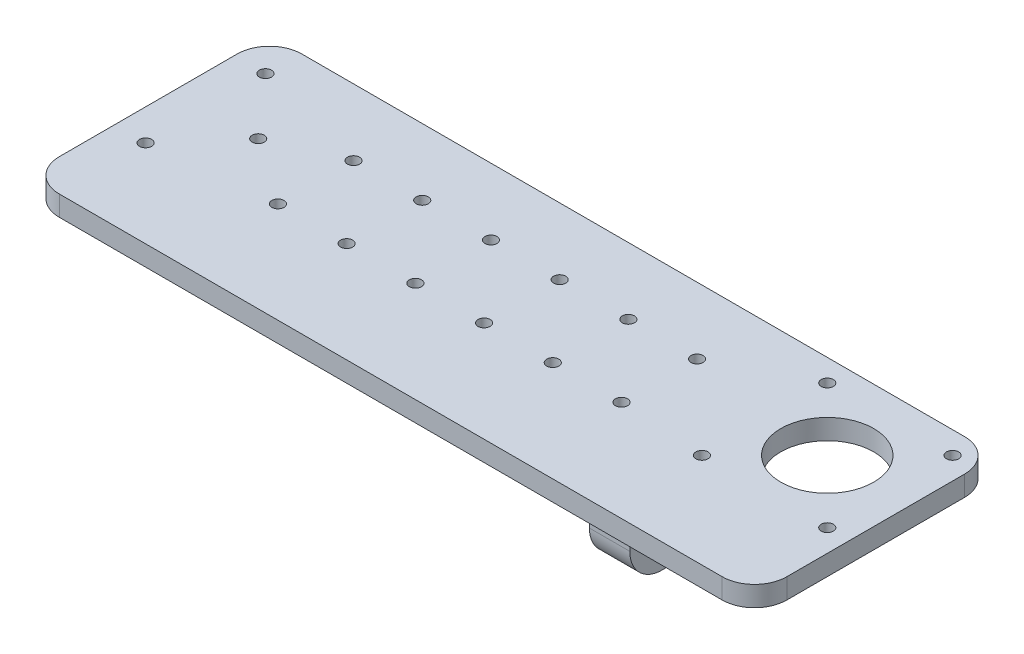
SolidWorks part; units mm, degrees
ref_plane "정면" through (0, 0, 0) normal (0, 0, 1) x (1, 0, 0)
ref_plane "윗면" through (0, 0, 0) normal (0, 1, 0) x (1, 0, 0)
ref_plane "우측면" through (0, 0, 0) normal (1, 0, 0) x (0, 0, -1)
sketch "스케치1" plane through (0, 0, 0) normal (0, 1, 0) x (1, 0, 0)
  line L0 (-53.3677, 28.2576) -> (-53.3677, -31.7424)
  line L1 (-53.3677, -31.7424) -> (126.6323, -31.7424)
  line L2 (126.6323, -31.7424) -> (126.6323, 28.2576)
  line L3 (126.6323, 28.2576) -> (-53.3677, 28.2576)
  circle A0 centre (105.6323, 7.2576) radius 11
  circle A2 centre (90.1323, 22.7576) radius 1.5
  circle A3 centre (121.1323, 22.7576) radius 1.5
  circle A4 centre (90.1323, -8.2424) radius 1.5
  circle A5 centre (121.1323, -8.2424) radius 1.5
  circle A6 centre (-32.6178, 4.7126) radius 1.5
  circle A7 centre (-45.6544, 19.5487) radius 1.5
  circle A8 centre (-45.6544, -10.1235) radius 1.5
  dimension "D4" = 31
  dimension "D1" = 180
  dimension "D3" = 60
  dimension "D5" = 31
extrude "보스-돌출3" add sketch "스케치1" along normal blind 5
sketch "스케치2" plane through (0, 5, 0) normal (0, 1, 0) x (1, 0, 0)
  line L2 (84.7825, 18.2576) -> (74.7825, 18.2576)
  line L3 (74.7825, 18.2576) -> (74.7825, -1.7424)
  line L4 (74.7825, -1.7424) -> (84.7825, -1.7424)
  line L5 (84.7825, -1.7424) -> (84.7825, 18.2576)
extrude "보스-돌출4" add sketch "스케치2" along normal blind 20
sketch "스케치4" plane through (74.7825, 0, 0) normal (-1, 0, 0) x (0, 0, 1)
  line L0 (1.7424, 25) -> (-8.2576, 25)
  line L1 (-18.2576, 25) -> (1.7424, 25) construction
  line L2 (-8.2576, 25) -> (-8.2576, 15)
  circle A0 centre (-8.2576, 15) radius 4
extrude "컷-돌출1" cut sketch "스케치4" against normal blind 20
sketch "스케치7" plane through (84.7825, 0, 0) normal (1, 0, 0) x (0, 0, -1)
  line L0 (18.2576, 25) -> (15.2576, 25)
  line L1 (-1.7424, 25) -> (18.2576, 25) construction
  line L2 (15.2576, 25) -> (15.2576, 5)
  line L3 (-1.7424, 5) -> (18.2576, 5) construction
  line L4 (15.2576, 5) -> (18.2576, 5)
  line L5 (18.2576, 5) -> (18.2576, 25)
  line L6 (-1.7424, 25) -> (1.2576, 25)
  line L7 (1.2576, 25) -> (1.2576, 5)
  line L8 (1.2576, 5) -> (-1.7424, 5)
  line L9 (-1.7424, 5) -> (-1.7424, 25)
  dimension "D1" = 3
  dimension "D2" = 3
sketch "스케치8" plane through (84.7825, 0, 0) normal (1, 0, 0) x (0, 0, -1)
  line L1 (15.2576, 25) -> (18.2576, 25)
  line L2 (15.2576, 25) -> (15.2576, 5)
  line L3 (15.2576, 5) -> (18.2576, 5)
  line L4 (18.2576, 25) -> (18.2576, 5)
  line L5 (1.2576, 25) -> (-1.7424, 25)
  line L6 (1.2576, 25) -> (1.2576, 5)
  line L7 (1.2576, 5) -> (-1.7424, 5)
  line L8 (-1.7424, 25) -> (-1.7424, 5)
extrude "컷-돌출4" cut sketch "스케치8" against normal blind 10
sketch "스케치9" plane through (84.7825, 0, 0) normal (1, 0, 0) x (0, 0, -1)
  line L0 (8.2576, 15) -> (1.7576, 15)
  line L1 (1.7576, 15) -> (1.7576, 5)
  line L2 (1.2576, 25) -> (15.2576, 25)
  line L3 (1.2576, 25) -> (1.2576, 5)
  line L4 (1.2576, 5) -> (15.2576, 5)
  line L5 (15.2576, 25) -> (15.2576, 5)
  line L6 (1.7576, 5) -> (1.7576, 25)
  line L8 (1.7576, 25) -> (-12.2424, 25)
  line L9 (1.7576, 25) -> (1.7576, 5)
  line L10 (1.7576, 5) -> (-12.2424, 5)
  line L11 (-12.2424, 25) -> (-12.2424, 5)
  circle A0 centre (-5.2424, 15) radius 4
  dimension "D3" = 8
  dimension "D1" = 14
  dimension "D2" = 6.5
  dimension "D4" = 7
sketch "스케치10" plane through (84.7825, 0, 0) normal (1, 0, 0) x (0, 0, -1)
  line L1 (-12.2424, 25) -> (1.7576, 25)
  line L2 (-12.2424, 25) -> (-12.2424, 5)
  line L3 (-12.2424, 5) -> (1.7576, 5)
  line L4 (1.7576, 25) -> (1.7576, 5)
extrude "보스-돌출5" add sketch "스케치10" against normal blind 10
extrude "컷-돌출5" cut sketch "스케치9" against normal blind 10 contours A0
sketch "스케치11" plane through (84.7825, 0, 0) normal (1, 0, 0) x (0, 0, -1)
  line L1 (-12.2424, 5) -> (15.2576, 5) construction
  line L3 (1.7576, 5) -> (15.2576, 5)
  line L4 (1.7576, 5) -> (1.7576, 25)
  line L5 (1.7576, 25) -> (15.2576, 25)
  line L6 (15.2576, 5) -> (15.2576, 25)
sketch "스케치12" plane through (84.7825, 0, 0) normal (1, 0, 0) x (0, 0, -1)
  line L1 (1.7576, 25) -> (15.2576, 25)
  line L2 (1.7576, 25) -> (1.7576, 5)
  line L3 (1.7576, 5) -> (15.2576, 5)
  line L4 (15.2576, 25) -> (15.2576, 5)
extrude "컷-돌출6" cut sketch "스케치12" against normal blind 10
sketch "스케치14" plane through (0, 5, 0) normal (0, 1, 0) x (1, 0, 0)
  line L0 (105.6323, 7.2576) -> (105.6323, 0.7576)
  line L1 (84.7825, 1.7576) -> (105.6323, 1.7576)
  dimension "D1" = 6.5
sketch "스케치15" plane through (84.7825, 0, 0) normal (1, 0, 0) x (0, 0, -1)
  line L0 (-12.2424, 5) -> (1.7576, 5) construction
  line L1 (1.7576, 25) -> (0.7576, 25)
  line L2 (1.7576, 25) -> (1.7576, 5)
  line L3 (1.7576, 5) -> (0.7576, 5)
  line L4 (0.7576, 25) -> (0.7576, 5)
  dimension "D1" = 1
extrude "컷-돌출7" cut sketch "스케치15" against normal blind 10
fillet "필렛5" radius 5 2 edges at (79.7825, 25, -0.7576) (79.7825, 25, 12.2424)
sketch "스케치16" plane through (0, 5, 0) normal (0, 1, 0) x (1, 0, 0)
  line L0 (105.6323, 7.2576) -> (105.6323, 0.7576)
sketch "스케치17" plane through (0, 5, 0) normal (0, 1, 0) x (1, 0, 0)
  line L0 (105.6323, 7.2576) -> (105.6323, -5.7424)
  line L1 (105.6323, -5.7424) -> (84.7825, -5.7424)
  line L2 (84.7825, -12.2424) -> (84.7825, 0.7576) construction
  line L3 (74.7825, 0.7576) -> (74.7825, -12.2424) construction
  line L4 (84.7825, -5.7424) -> (74.7825, -5.7424)
  line L5 (84.7825, -5.7424) -> (84.7825, 3.2576)
  line L6 (84.7825, 3.2576) -> (74.7825, 3.2576)
  line L7 (74.7825, -5.7424) -> (74.7825, 3.2576)
  line L9 (84.7825, -5.7424) -> (74.7825, -5.7424)
  line L10 (84.7825, -5.7424) -> (84.7825, -14.7424)
  line L11 (84.7825, -14.7424) -> (74.7825, -14.7424)
  line L12 (74.7825, -5.7424) -> (74.7825, -14.7424)
  dimension "D1" = 9
  dimension "D2" = 9
sketch "스케치20" plane through (74.7825, 0, 0) normal (-1, 0, 0) x (0, 0, 1)
  line L1 (-3.2576, 5) -> (-1.0985, 5)
  line L2 (-3.2576, 5) -> (-3.2576, 27.106)
  line L3 (-3.2576, 27.106) -> (-1.0985, 27.106)
  line L4 (-1.0985, 5) -> (-1.0985, 27.106)
sketch "스케치21" plane through (0, 5, 0) normal (0, 1, 0) x (1, 0, 0)
  line L1 (84.7825, -14.7424) -> (74.7825, -14.7424)
  line L2 (84.7825, -14.7424) -> (84.7825, 3.2576)
  line L3 (84.7825, 3.2576) -> (74.7825, 3.2576)
  line L4 (74.7825, -14.7424) -> (74.7825, 3.2576)
extrude "보스-돌출6" add sketch "스케치21" along normal blind 20
sketch "스케치23" plane through (84.7825, 0, 0) normal (1, 0, 0) x (0, 0, -1)
  line L1 (-14.7424, 25) -> (3.2576, 25) construction
  circle A0 centre (-5.7424, 15) radius 4
  dimension "D1" = 10
extrude "컷-돌출9" cut sketch "스케치23" against normal blind 20
fillet "필렛8" radius 8 1 edges at (79.7825, 5, 14.7424)
sketch "스케치24" plane through (0, 5, 0) normal (0, 1, 0) x (1, 0, 0)
  line L0 (105.6323, 7.2576) -> (105.6323, 0.7576)
sketch "스케치25" plane through (0, 5, 0) normal (0, 1, 0) x (1, 0, 0)
  line L1 (84.7825, 3.2576) -> (73.4713, 3.2576)
  line L2 (84.7825, 3.2576) -> (84.7825, 1.7576)
  line L3 (84.7825, 1.7576) -> (73.4713, 1.7576)
  line L4 (73.4713, 3.2576) -> (73.4713, 1.7576)
extrude "컷-돌출10" cut sketch "스케치25" along normal blind 20
fillet "필렛9" radius 8 2 edges at (79.7825, 25, 14.7424) (79.7825, 25, -1.7576)
sketch "스케치28" plane through (0, 5, 0) normal (0, 1, 0) x (1, 0, 0)
  line L1 (84.7825, 1.7576) -> (74.7825, 1.7576)
  line L2 (84.7825, 1.7576) -> (84.7825, -14.7424)
  line L3 (84.7825, -14.7424) -> (74.7825, -14.7424)
  line L4 (74.7825, 1.7576) -> (74.7825, -14.7424)
extrude "보스-돌출7" add sketch "스케치28" against normal blind 25
sketch "스케치29" plane through (84.7825, 0, 0) normal (1, 0, 0) x (0, 0, -1)
  line L0 (-1.7424, 15) -> (-1.7424, -20)
  line L1 (-14.7424, -20) -> (1.7576, -20) construction
  line L2 (-9.7424, 15) -> (-9.7424, -20)
  line L3 (-5.7424, 15) -> (-5.7424, -15.838)
  circle A0 centre (-5.7424, 15) radius 4 construction
  circle A1 centre (-5.7424, -10) radius 4
  dimension "D1" = 10
sketch "스케치30" plane through (84.7825, 0, 0) normal (1, 0, 0) x (0, 0, -1)
  circle A0 centre (-5.7424, -10) radius 3.9991
sketch "스케치31" plane through (0, 5, 0) normal (0, 1, 0) x (1, 0, 0)
  line L1 (85.7781, -25.2023) -> (58.1481, -25.2023)
  line L2 (85.7781, -25.2023) -> (85.7781, 8.1404)
  line L3 (85.7781, 8.1404) -> (58.1481, 8.1404)
  line L4 (58.1481, -25.2023) -> (58.1481, 8.1404)
extrude "컷-돌출12" cut sketch "스케치31" along normal blind 20
sketch "스케치33" plane through (0, 0, 14.7424) normal (0, 0, 1) x (1, 0, 0)
  line L1 (84.7825, -20) -> (74.7825, -20)
  line L2 (84.7825, -20) -> (84.7825, 0)
  line L3 (84.7825, 0) -> (74.7825, 0)
  line L4 (74.7825, -20) -> (74.7825, 0)
extrude "보스-돌출8" add sketch "스케치33" along normal blind 6
sketch "스케치34" plane through (0, 0, -1.7576) normal (0, 0, -1) x (-1, 0, 0)
  line L1 (-74.7825, -20) -> (-84.7825, -20)
  line L2 (-74.7825, -20) -> (-74.7825, 0)
  line L3 (-74.7825, 0) -> (-84.7825, 0)
  line L4 (-84.7825, -20) -> (-84.7825, 0)
extrude "컷-돌출13" cut sketch "스케치34" against normal blind 6
sketch "스케치35" plane through (84.7825, 0, 0) normal (1, 0, 0) x (0, 0, -1)
  line L0 (-20.7424, -20) -> (-20.7424, 0) construction
  circle A0 centre (-11.7424, -10) radius 4
  dimension "D1" = 9
extrude "컷-돌출14" cut sketch "스케치35" against normal blind 10
fillet "필렛11" radius 8 3 edges at (79.7825, 0, 20.7424) (79.7825, -20, 4.2424) (79.7825, -20, 20.7424)
sketch "스케치36" plane through (0, 0, 0) normal (0, -1, 0) x (1, 0, 0)
  circle A0 centre (-16.1941, 6.8229) radius 1.5
  circle A1 centre (-16.1141, -11.7971) radius 1.5
  circle A2 centre (-32.6178, -4.7126) radius 1.5 construction
  circle A3 centre (0.8059, 6.8229) radius 1.5
  circle A4 centre (0.8859, -11.7971) radius 1.5
  circle A5 centre (17.8059, 6.8229) radius 1.5
  circle A6 centre (17.8859, -11.7971) radius 1.5
  circle A7 centre (34.8059, 6.8229) radius 1.5
  circle A8 centre (34.8859, -11.7971) radius 1.5
  circle A9 centre (51.8059, 6.8229) radius 1.5
  circle A10 centre (51.8859, -11.7971) radius 1.5
  circle A11 centre (68.8059, 6.8229) radius 1.5
  circle A12 centre (68.8859, -11.7971) radius 1.5
  dimension "D1" = 17.96
  dimension "D2" = 20.07
  dimension "D3" = 18.62
  dimension "D4" = 6
extrude "컷-돌출15" cut sketch "스케치36" against normal blind 10
sketch "스케치37" plane through (84.7825, 0, 0) normal (1, 0, 0) x (0, 0, -1)
  circle A0 centre (-11.7424, -10) radius 4.5
extrude "컷-돌출16" cut sketch "스케치37" against normal blind 10
sketch "스케치38" plane through (0, 0, 0) normal (0, -1, 0) x (1, 0, 0)
  circle A0 centre (105.6323, -7.2576) radius 11.5
extrude "컷-돌출17" cut sketch "스케치38" against normal blind 10
sketch "스케치39" plane through (0, 0, 4.2424) normal (0, 0, -1) x (-1, 0, 0)
  line L1 (-84.7825, 15) -> (-84.7825, -15.838) construction
  circle A0 centre (-79.7825, -9.1063) radius 1.5
  dimension "D1" = 5
extrude "컷-돌출18" cut sketch "스케치39" against normal blind 10
sketch "스케치40" plane through (0, 5, 0) normal (0, 1, 0) x (1, 0, 0)
  line L0 (126.6323, 28.2576) -> (121.6323, 28.2576)
  line L1 (126.6323, 28.2576) -> (-53.3677, 28.2576) construction
  line L2 (121.6323, 28.2576) -> (126.6323, 23.2576)
  line L3 (126.6323, -31.7424) -> (126.6323, 28.2576) construction
  line L4 (126.6323, 23.2576) -> (126.6323, 28.2576)
  line L5 (126.6323, -31.7424) -> (121.6323, -31.7424)
  line L6 (-53.3677, -31.7424) -> (126.6323, -31.7424) construction
  line L7 (126.6323, -31.7424) -> (126.6323, -26.7424)
  line L8 (126.6323, -26.7424) -> (121.6323, -31.7424)
fillet "필렛13" radius 8 4 edges at (-53.3677, 2.5, -28.2576) (-53.3677, 2.5, 31.7424) (126.6323, 2.5, 31.7424) (126.6323, 2.5, -28.2576)
